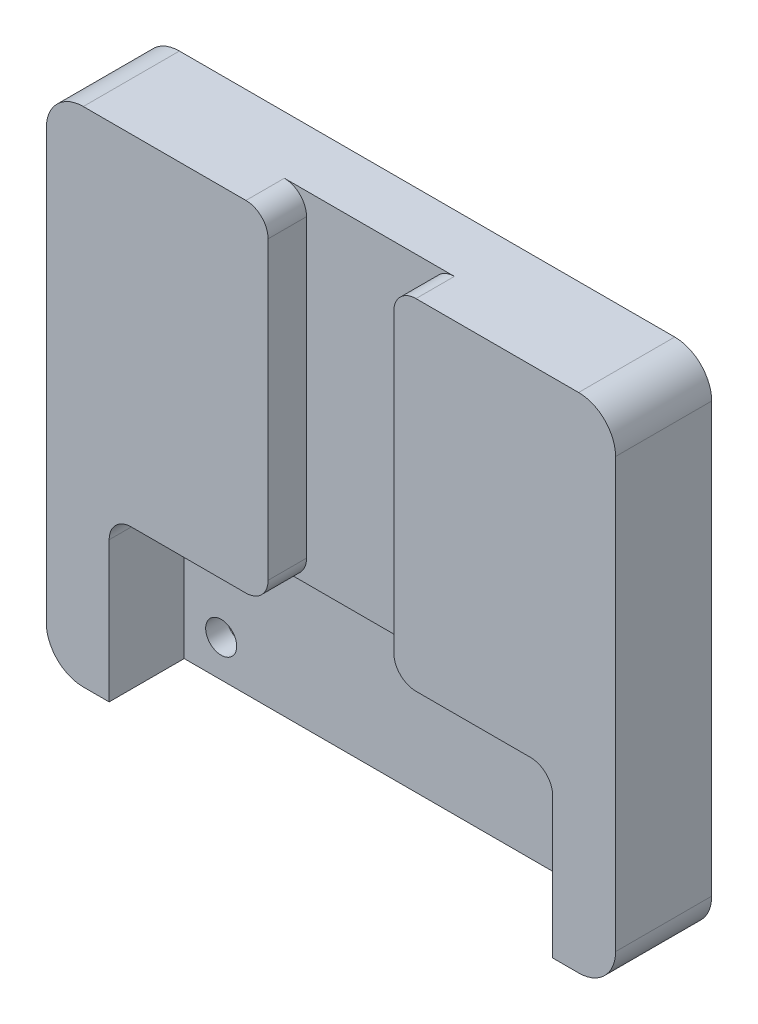
SolidWorks part; units mm, degrees
ref_plane "前视基准面" through (0, 0, 0) normal (1, 0, 0) x (0, 1, 0)
ref_plane "上视基准面" through (0, 0, 0) normal (0, 0, 1) x (0, 1, 0)
ref_plane "右视基准面" through (0, 0, 0) normal (0, 1, 0) x (-1, 0, 0)
other "Configuration Table"
sketch "草图1" plane through (0, 0, 0) normal (1, 0, 0) x (0, 1, 0)
  line L1 (0, 0) -> (68, 0)
  line L2 (0, 0) -> (0, 13)
  line L3 (0, 13) -> (68, 13)
  line L4 (68, 0) -> (68, 13)
  dimension "D1" = 13
  dimension "D2" = 68
extrude "凸台-拉伸1" add sketch "草图1" along normal blind 77
sketch "草图2" plane through (0, 0, 13) normal (0, 0, 1) x (1, 0, 0)
  line L0 (77, 0) -> (0, 0) construction
  line L1 (8.5, 0) -> (68.5, 0)
  line L2 (8.5, 0) -> (8.5, 22)
  line L3 (8.5, 22) -> (68.5, 22)
  line L4 (68.5, 0) -> (68.5, 22)
  line L5 (0, 68) -> (0, 0) construction
  dimension "D1" = 60
  dimension "D2" = 8.5
  dimension "D3" = 22
extrude "切除-拉伸1" cut sketch "草图2" against normal blind 10.15
fillet "圆角1" radius 5 4 edges at (0, 68, 6.5) (77, 68, 6.5) (0, 0, 6.5) (77, 0, 6.5)
sketch "草图3" plane through (0, 0, 13) normal (0, 0, 1) x (1, 0, 0)
  line L0 (72, 68) -> (5, 68) construction
  line L1 (30, 68) -> (47, 68)
  line L2 (30, 68) -> (30, 22)
  line L3 (30, 22) -> (47, 22)
  line L4 (47, 68) -> (47, 22)
  line L5 (68.5, 22) -> (8.5, 22) construction
  line L6 (77, 63) -> (77, 5) construction
  line L7 (0, 63) -> (0, 5) construction
  dimension "D1" = 30
  dimension "D2" = 30
extrude "切除-拉伸2" cut sketch "草图3" against normal blind 5.2
fillet "圆角2" radius 3 6 edges at (68.5, 22, 7.925) (8.5, 22, 7.925) (47, 68, 10.4) (30, 68, 10.4) (30, 22, 10.4) (47, 22, 10.4)
chamfer "倒角2" [suppressed] distance 1 angle 45
sketch "草图5" plane through (0, 0, 2.85) normal (0, 0, 1) x (1, 0, 0)
  line L0 (8.5, 0) -> (68.5, 0) construction
  line L1 (63.5, 5) -> (13.5, 5) construction
  line L2 (68.5, 0) -> (68.5, 19) construction
  line L3 (63.5, 5) -> (63.5, 19) construction
  circle A0 centre (63.5, 5) radius 2.1
  circle A1 centre (13.5, 5) radius 2.1
  circle A2 centre (13.5, 19) radius 2.1
  circle A3 centre (63.5, 19) radius 2.1
  dimension "D1" = 4.2
  dimension "D2" = 5
  dimension "D3" = 5
  dimension "D4" = 2
  dimension "D6" = 50
  dimension "D7" = 14
  dimension "D5" = 2
extrude "切除-拉伸4" cut sketch "草图5" against normal blind 4.6
sketch "草图9" plane through (0, 0, 13) normal (0, 0, 1) x (1, 0, 0)
  circle A0 centre (68.7123, 31.278) radius 2.1
  circle A1 centre (53.7123, 31.278) radius 2.1
  circle A2 centre (23.7123, 31.278) radius 2.1
  circle A3 centre (8.7123, 31.278) radius 2.1
  dimension "D1" = 4.2
  dimension "D2" = 4.2
  dimension "D3" = 4.2
  dimension "D4" = 4.2
extrude "切除-拉伸5" [suppressed] cut sketch "草图9" against normal blind 4.6
